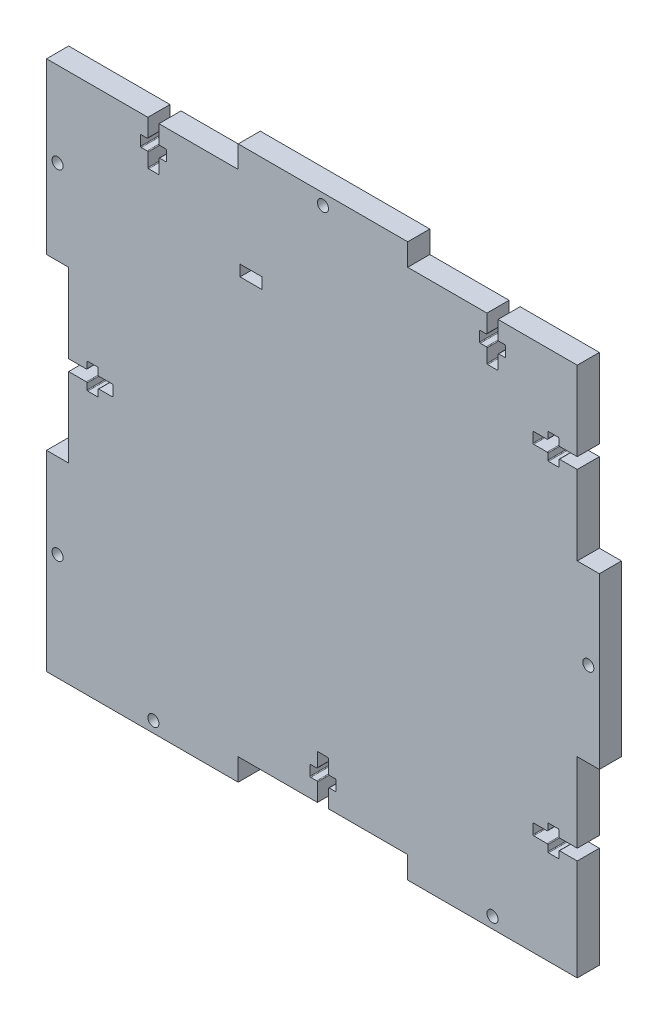
SolidWorks part; units mm, degrees
ref_plane "Front Plane" through (0, 0, 0) normal (0, 0, 1) x (1, 0, 0)
ref_plane "Top Plane" through (0, 0, 0) normal (0, 1, 0) x (1, 0, 0)
ref_plane "Right Plane" through (0, 0, 0) normal (1, 0, 0) x (0, 0, -1)
sketch "Sketch1" plane through (0, 0, 0) normal (0, 0, 1) x (1, 0, 0)
  line L0 (-69, 69) -> (-23, 69)
  line L5 (-75, -75) -> (75, -75) construction
  line L6 (-75, -75) -> (-75, 75) construction
  line L7 (-75, 75) -> (75, 75) construction
  line L8 (75, -75) -> (75, 75) construction
  line L9 (75, 23) -> (69, 23)
  line L10 (69, -23) -> (75, -23)
  line L11 (-69, -69) -> (69, -69) construction
  line L12 (-69, -69) -> (-69, 69) construction
  line L13 (-69, 69) -> (69, 69) construction
  line L14 (69, -69) -> (69, 69) construction
  line L15 (-69, -69) -> (69, 69) construction
  line L16 (69, -69) -> (69, -23)
  line L17 (-23, 69) -> (-23, 75)
  line L18 (-23, 75) -> (23, 75)
  line L19 (23, 75) -> (23, 69)
  line L20 (23, 69) -> (69, 69)
  line L21 (75, -23) -> (75, 23)
  line L22 (69, 23) -> (69, 69)
  line L23 (-75, 23) -> (-69, 23)
  line L24 (-69, 69) -> (-75, 69)
  line L25 (-75, 69) -> (-75, 23)
  line L26 (69, -69) -> (69, -75)
  line L27 (69, -75) -> (23, -75)
  line L28 (23, -75) -> (23, -69)
  line L29 (23, -69) -> (-23, -69)
  line L30 (-23, -69) -> (-23, -75)
  line L31 (-23, -75) -> (-69, -75)
  line L32 (-69, -75) -> (-69, -69) construction
  line L33 (-69, 23) -> (-69, -23)
  line L34 (-69, -23) -> (-75, -23)
  line L35 (-75, -23) -> (-75, -69)
  line L36 (-75, -69) -> (-69, -69) construction
  line L37 (-46, 69) -> (-46, -75) construction
  line L38 (-69, 69) -> (69, -69) construction
  line L39 (-75, -75) -> (-69, -75)
  line L40 (-75, -75) -> (-75, -69)
  point P0 (0, 0)
  point P6 (-7, -7)
  point P26 (0, -75)
  point P27 (-75, 0)
  dimension "D1" = 150
  dimension "D2" = 150
  dimension "D5" = 46
  dimension "D3" = 6
  dimension "D6" = 6
  dimension "D7" = 6
extrude "Box Side" add sketch "Sketch1" along normal blind 6
sketch "Sketch2" plane through (0, 0, 6) normal (0, 0, 1) x (1, 0, 0)
  line L0 (23, 72) -> (-23, 72) construction
  line L1 (23, 75) -> (23, 69) construction
  line L2 (-23, 69) -> (-23, 75) construction
  line L3 (-46, 69) -> (-46, -75) construction
  line L5 (0, 75) -> (0, 69) construction
  line L6 (-23, 75) -> (23, 75) construction
  line L7 (-69, 69) -> (69, 69) construction
  line L16 (-46, 69) -> (-46, -75) construction
  line L21 (0, -69) -> (0, 69) construction
  line L35 (-69, 69) -> (-23, 69) construction
  line L36 (-44.5, 69) -> (-44.5, 64.2)
  line L37 (-44.3, 64) -> (-42.7, 64)
  line L38 (-42.5, 63.8) -> (-42.5, 61.2)
  line L39 (-42.7, 61) -> (-44.3, 61)
  line L40 (-44.5, 60.8) -> (-44.5, 57.2)
  line L46 (-44.7, 57) -> (-47.3, 57)
  line L48 (-44.5, 69) -> (-47.5, 69)
  line L51 (-47.5, 60.8) -> (-47.5, 57.2)
  line L52 (-49.3, 61) -> (-47.7, 61)
  line L53 (-49.5, 63.8) -> (-49.5, 61.2)
  line L54 (-47.7, 64) -> (-49.3, 64)
  line L55 (-47.5, 69) -> (-47.5, 64.2)
  line L56 (47.5, 69) -> (47.5, 64.2)
  line L57 (47.7, 64) -> (49.3, 64)
  line L58 (49.5, 63.8) -> (49.5, 61.2)
  line L59 (49.3, 61) -> (47.7, 61)
  line L60 (47.5, 60.8) -> (47.5, 57.2)
  line L61 (44.5, 69) -> (47.5, 69)
  line L62 (44.7, 57) -> (47.3, 57)
  line L63 (44.5, 60.8) -> (44.5, 57.2)
  line L64 (42.7, 61) -> (44.3, 61)
  line L65 (42.5, 63.8) -> (42.5, 61.2)
  line L66 (44.3, 64) -> (42.7, 64)
  line L67 (44.5, 69) -> (44.5, 64.2)
  line L68 (-69, -69) -> (69, 69) construction
  line L69 (-69, -69) -> (69, 69) construction
  line L70 (75, 0) -> (69, 0) construction
  line L71 (72, 23) -> (72, -23) construction
  line L72 (69, 44.5) -> (64.2, 44.5)
  line L73 (64, 44.3) -> (64, 42.7)
  line L74 (63.8, 42.5) -> (61.2, 42.5)
  line L75 (61, 42.7) -> (61, 44.3)
  line L76 (60.8, 44.5) -> (57.2, 44.5)
  line L77 (57, 44.7) -> (57, 47.3)
  line L78 (69, 44.5) -> (69, 47.5)
  line L79 (60.8, 47.5) -> (57.2, 47.5)
  line L80 (61, 49.3) -> (61, 47.7)
  line L81 (63.8, 49.5) -> (61.2, 49.5)
  line L82 (64, 47.7) -> (64, 49.3)
  line L83 (69, 47.5) -> (64.2, 47.5)
  line L84 (69, -47.5) -> (64.2, -47.5)
  line L85 (64, -47.7) -> (64, -49.3)
  line L86 (63.8, -49.5) -> (61.2, -49.5)
  line L87 (61, -49.3) -> (61, -47.7)
  line L88 (60.8, -47.5) -> (57.2, -47.5)
  line L89 (69, -44.5) -> (69, -47.5)
  line L90 (57, -44.7) -> (57, -47.3)
  line L91 (60.8, -44.5) -> (57.2, -44.5)
  line L92 (61, -42.7) -> (61, -44.3)
  line L93 (63.8, -42.5) -> (61.2, -42.5)
  line L94 (64, -44.3) -> (64, -42.7)
  line L95 (69, -44.5) -> (64.2, -44.5)
  line L120 (-69, 69) -> (69, -69) construction
  line L121 (-69, 69) -> (69, -69) construction
  line L122 (-1.5, -69) -> (1.5, -69)
  line L123 (-23, -69) -> (23, -69) construction
  line L124 (1.5, -69) -> (1.5, -64.2)
  line L125 (1.7, -64) -> (3.3, -64)
  line L126 (3.5, -63.8) -> (3.5, -61.2)
  line L127 (3.3, -61) -> (1.7, -61)
  line L128 (1.5, -60.8) -> (1.5, -57.2)
  line L129 (1.3, -57) -> (-1.3, -57)
  line L130 (-1.5, -60.8) -> (-1.5, -57.2)
  line L131 (-3.3, -61) -> (-1.7, -61)
  line L132 (-3.5, -63.8) -> (-3.5, -61.2)
  line L133 (-1.7, -64) -> (-3.3, -64)
  line L134 (-1.5, -69) -> (-1.5, -64.2)
  line L135 (-69, -1.5) -> (-64.2, -1.5)
  line L136 (-64, -1.7) -> (-64, -3.3)
  line L137 (-63.8, -3.5) -> (-61.2, -3.5)
  line L138 (-61, -3.3) -> (-61, -1.7)
  line L139 (-60.8, -1.5) -> (-57.2, -1.5)
  line L140 (-57, 1.3) -> (-57, -1.3)
  line L141 (-60.8, 1.5) -> (-57.2, 1.5)
  line L142 (-61, 3.3) -> (-61, 1.7)
  line L143 (-63.8, 3.5) -> (-61.2, 3.5)
  line L144 (-64, 1.7) -> (-64, 3.3)
  line L145 (-69, 1.5) -> (-64.2, 1.5)
  line L146 (-69, -1.5) -> (-69, 1.5)
  line L147 (-69, -72) -> (-23, -72) construction
  line L148 (-23, 69) -> (-75, 69) construction
  line L149 (-23, -75) -> (-23, -69) construction
  line L150 (-69, -69) -> (-69, -75) construction
  line L151 (-75, -75) -> (-23, -75) construction
  circle A0 centre (0, 72) radius 1.5
  arc A1 (-44.5, 57.2) -> (-44.7, 57) centre (-44.7, 57.2) cw
  arc A2 (-44.3, 61) -> (-44.5, 60.8) centre (-44.3, 60.8) ccw
  arc A3 (-42.5, 61.2) -> (-42.7, 61) centre (-42.7, 61.2) cw
  arc A4 (-42.7, 64) -> (-42.5, 63.8) centre (-42.7, 63.8) cw
  arc A5 (-44.5, 64.2) -> (-44.3, 64) centre (-44.3, 64.2) ccw
  arc A6 (-47.5, 64.2) -> (-47.7, 64) centre (-47.7, 64.2) cw
  arc A7 (-49.3, 64) -> (-49.5, 63.8) centre (-49.3, 63.8) ccw
  arc A8 (-49.5, 61.2) -> (-49.3, 61) centre (-49.3, 61.2) ccw
  arc A9 (-47.7, 61) -> (-47.5, 60.8) centre (-47.7, 60.8) cw
  arc A10 (-47.5, 57.2) -> (-47.3, 57) centre (-47.3, 57.2) ccw
  arc A11 (47.5, 57.2) -> (47.3, 57) centre (47.3, 57.2) cw
  arc A12 (47.7, 61) -> (47.5, 60.8) centre (47.7, 60.8) ccw
  arc A13 (49.5, 61.2) -> (49.3, 61) centre (49.3, 61.2) cw
  arc A14 (49.3, 64) -> (49.5, 63.8) centre (49.3, 63.8) cw
  arc A15 (47.5, 64.2) -> (47.7, 64) centre (47.7, 64.2) ccw
  arc A16 (44.5, 64.2) -> (44.3, 64) centre (44.3, 64.2) cw
  arc A17 (42.7, 64) -> (42.5, 63.8) centre (42.7, 63.8) ccw
  arc A18 (42.5, 61.2) -> (42.7, 61) centre (42.7, 61.2) ccw
  arc A19 (44.3, 61) -> (44.5, 60.8) centre (44.3, 60.8) cw
  arc A20 (44.5, 57.2) -> (44.7, 57) centre (44.7, 57.2) ccw
  arc A21 (57.2, 44.5) -> (57, 44.7) centre (57.2, 44.7) cw
  arc A22 (61, 44.3) -> (60.8, 44.5) centre (60.8, 44.3) ccw
  arc A23 (61.2, 42.5) -> (61, 42.7) centre (61.2, 42.7) cw
  arc A24 (64, 42.7) -> (63.8, 42.5) centre (63.8, 42.7) cw
  arc A25 (64.2, 44.5) -> (64, 44.3) centre (64.2, 44.3) ccw
  arc A26 (64.2, 47.5) -> (64, 47.7) centre (64.2, 47.7) cw
  arc A27 (64, 49.3) -> (63.8, 49.5) centre (63.8, 49.3) ccw
  arc A28 (61.2, 49.5) -> (61, 49.3) centre (61.2, 49.3) ccw
  arc A29 (61, 47.7) -> (60.8, 47.5) centre (60.8, 47.7) cw
  arc A30 (57.2, 47.5) -> (57, 47.3) centre (57.2, 47.3) ccw
  arc A31 (57.2, -47.5) -> (57, -47.3) centre (57.2, -47.3) cw
  arc A32 (61, -47.7) -> (60.8, -47.5) centre (60.8, -47.7) ccw
  arc A33 (61.2, -49.5) -> (61, -49.3) centre (61.2, -49.3) cw
  arc A34 (64, -49.3) -> (63.8, -49.5) centre (63.8, -49.3) cw
  arc A35 (64.2, -47.5) -> (64, -47.7) centre (64.2, -47.7) ccw
  arc A36 (64.2, -44.5) -> (64, -44.3) centre (64.2, -44.3) cw
  arc A37 (64, -42.7) -> (63.8, -42.5) centre (63.8, -42.7) ccw
  arc A38 (61.2, -42.5) -> (61, -42.7) centre (61.2, -42.7) ccw
  arc A39 (61, -44.3) -> (60.8, -44.5) centre (60.8, -44.3) cw
  arc A40 (57.2, -44.5) -> (57, -44.7) centre (57.2, -44.7) ccw
  circle A41 centre (72, 0) radius 1.5
  arc A62 (1.5, -57.2) -> (1.3, -57) centre (1.3, -57.2) ccw
  arc A63 (1.7, -61) -> (1.5, -60.8) centre (1.7, -60.8) cw
  arc A64 (3.5, -61.2) -> (3.3, -61) centre (3.3, -61.2) ccw
  arc A65 (3.3, -64) -> (3.5, -63.8) centre (3.3, -63.8) ccw
  arc A66 (1.5, -64.2) -> (1.7, -64) centre (1.7, -64.2) cw
  arc A67 (-1.5, -64.2) -> (-1.7, -64) centre (-1.7, -64.2) ccw
  arc A68 (-3.3, -64) -> (-3.5, -63.8) centre (-3.3, -63.8) cw
  arc A69 (-3.5, -61.2) -> (-3.3, -61) centre (-3.3, -61.2) cw
  arc A70 (-1.7, -61) -> (-1.5, -60.8) centre (-1.7, -60.8) ccw
  arc A71 (-1.5, -57.2) -> (-1.3, -57) centre (-1.3, -57.2) cw
  arc A72 (-57.2, -1.5) -> (-57, -1.3) centre (-57.2, -1.3) ccw
  arc A73 (-61, -1.7) -> (-60.8, -1.5) centre (-60.8, -1.7) cw
  arc A74 (-61.2, -3.5) -> (-61, -3.3) centre (-61.2, -3.3) ccw
  arc A75 (-64, -3.3) -> (-63.8, -3.5) centre (-63.8, -3.3) ccw
  arc A76 (-64.2, -1.5) -> (-64, -1.7) centre (-64.2, -1.7) cw
  arc A77 (-64.2, 1.5) -> (-64, 1.7) centre (-64.2, 1.7) ccw
  arc A78 (-64, 3.3) -> (-63.8, 3.5) centre (-63.8, 3.3) cw
  arc A79 (-61.2, 3.5) -> (-61, 3.3) centre (-61.2, 3.3) cw
  arc A80 (-61, 1.7) -> (-60.8, 1.5) centre (-60.8, 1.7) ccw
  arc A81 (-57.2, 1.5) -> (-57, 1.3) centre (-57.2, 1.3) cw
  circle A82 centre (-46, -72) radius 1.5
  circle A83 centre (46, -72) radius 1.5
  circle A84 centre (-72, 46) radius 1.5
  circle A85 centre (-72, -46) radius 1.5
  point P6 (0, 72)
  point P38 (0, 0)
  point P56 (-46, 57)
  point P88 (46, 57)
  point P161 (57, 46)
  point P162 (57, -46)
  point P198 (0, -57)
  point P231 (-57, 0)
  point P234 (-42.5, 62.5)
  dimension "D1" = 3
  dimension "D2" = 0.2
  dimension "D8" = 0.2
  dimension "D14" = 3
  dimension "D4" = 3
  dimension "D7" = 1.5
  dimension "D10" = 3
  dimension "D12" = 1.5
  dimension "D9" = 12
  dimension "D11" = 5
  dimension "D13" = 7
  dimension "D3" = 12
  dimension "D5" = 7
  dimension "D6" = 5
extrude "Screw Cut-outs" cut sketch "Sketch2" against normal through all
sketch "Sketch3" plane through (0, 0, 6) normal (0, 0, 1) x (1, 0, 0)
  line L0 (-75, 69) -> (-75, 23) construction
  line L1 (-22.5, 44) -> (-16.5, 44)
  line L2 (-22.5, 44) -> (-22.5, 47)
  line L3 (-22.5, 47) -> (-16.5, 47)
  line L4 (-16.5, 44) -> (-16.5, 47)
  line L5 (23, 75) -> (-23, 75) construction
  dimension "D1" = 6
  dimension "D2" = 3
  dimension "D3" = 52.5
  dimension "D4" = 28
extrude "Cut-Extrude1" cut sketch "Sketch3" against normal through all
equation "\"filletRadius\"=0.2"
equation "\"D8@Sketch2\"=\"filletRadius\""
equation "\"D2@Sketch2\"=\"filletRadius\""
equation "\"fingerWidth\"= 46"
equation "\"D5@Sketch1\"=\"fingerWidth\""
equation "\"wallThickness\"= 6"
equation "\"D3@Sketch1\" = \"wallThickness\""
equation "\"D6@Sketch1\" = \"wallThickness\""
equation "\"D7@Sketch1\" = \"wallThickness\""
equation "\"D1@Box Side\" = \"wallThickness\""
equation "\"M3\"= 3"
equation "\"D14@Sketch2\"=\"M3\""
equation "\"D1@Sketch2\"=\"M3\""
equation "\"D12@Sketch2\"=\"M3\"/2"
equation "\"nutThickness\"=3"
equation "\"D10@Sketch2\" = \"nutThickness\""
equation "\"boltLength\"= 12"
equation "\"D9@Sketch2\" = \"boltLength\""
equation "\"distanceToNut\"= 5"
equation "\"D11@Sketch2\" = \"distanceToNut\""
equation "\"D13@Sketch2\" = \"nutWidth\""
equation "\"D7@Sketch2\"=\"M3\"/2"
equation "\"D4@Sketch2\" = \"nutThickness\""
equation "\"D3@Sketch2\" = \"boltLength\""
equation "\"D5@Sketch2\" = \"nutWidth\""
equation "\"D6@Sketch2\" = \"distanceToNut\""
equation "\"sideLength\"=150"
equation "\"D1@Sketch1\"=\"sideLength\""
equation "\"D2@Sketch1\"=\"sideLength\""
equation "\"nutWidth\"=7"
